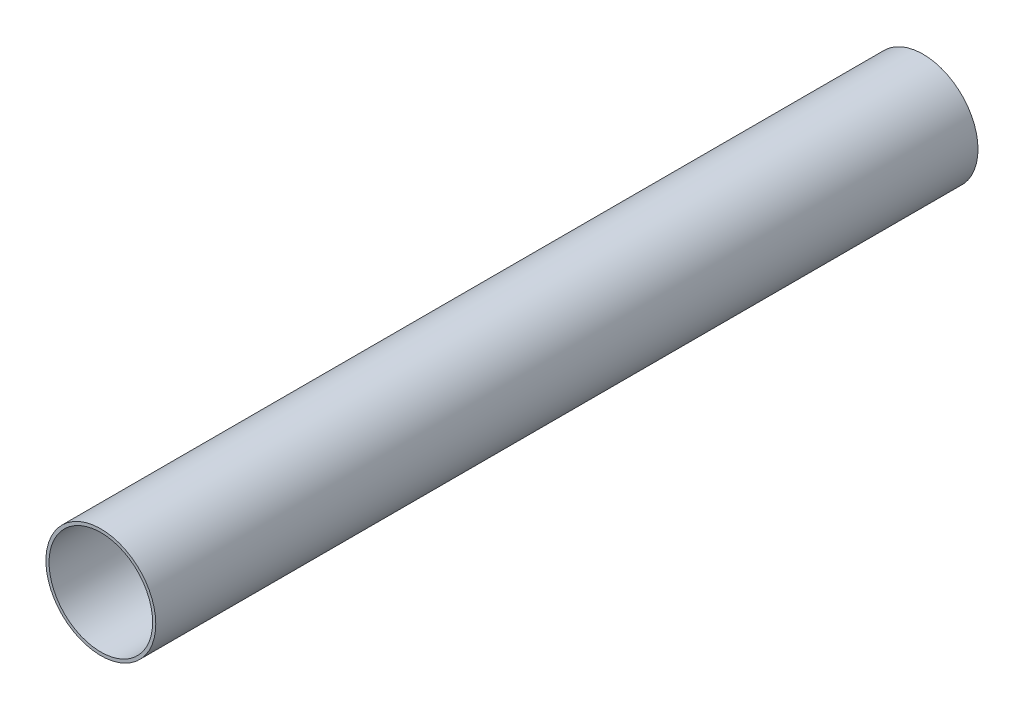
SolidWorks part; units mm, degrees
ref_plane "Front Plane" through (0, 0, 0) normal (0, 0, 1) x (1, 0, 0)
ref_plane "Top Plane" through (0, 0, 0) normal (0, 1, 0) x (1, 0, 0)
ref_plane "Right Plane" through (0, 0, 0) normal (1, 0, 0) x (0, 0, -1)
sketch "Sketch2" plane through (0, 0, 0) normal (0, 0, 1) x (1, 0, 0)
  circle A0 centre (0, 0) radius 44.1325
  circle A1 centre (0, 0) radius 41.5925
  dimension "D1" = 88.265
  dimension "D2" = 2.54
extrude "Boss-Extrude1" add sketch "Sketch2" along normal blind 660.4
